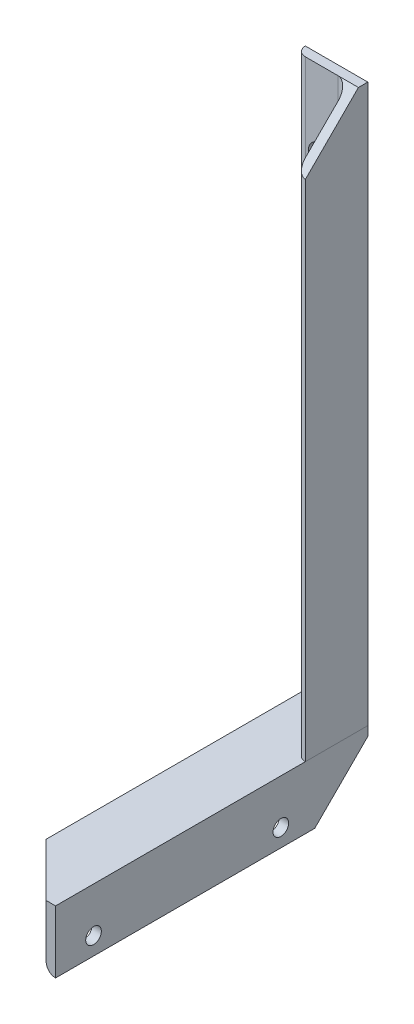
SolidWorks part; units mm, degrees
ref_plane "Plano frontal" through (0, 0, 0) normal (0, 0, 1) x (1, 0, 0)
ref_plane "Plano superior" through (0, 0, 0) normal (0, 1, 0) x (1, 0, 0)
ref_plane "Plano direito" through (0, 0, 0) normal (1, 0, 0) x (0, 0, -1)
sketch3d "3DSketch3"
  line L0 (-88.2895, 161.7817, 0) -> (-88.2895, -16.7183, 0)
  line L1 (-88.2895, -16.7183, 0) -> (-88.2895, -16.7183, 100)
  point P3 (-88.2895, 161.7817, 0)
  point P4 (0, 0, 0)
  dimension "D1" = 178.5
other "L angle (equal) 20X20X3(3)"
ref_plane "Plano1" through (-88.2895, 161.7817, 0) normal (0, 1, 0) x (-1, 0, 0)
sketch "Sketch1" plane through (-88.2895, 161.7817, 0) normal (0, 1, 0) x (-1, 0, 0)
  line L0 (0, 20) -> (0, 0)
  line L2 (3, 17) -> (3, 6.5)
  line L3 (6.5, 3) -> (17, 3)
  line L5 (20, 0) -> (0, 0)
  arc A0 (3, 17) -> (0, 20) centre (0, 17) ccw
  arc A1 (20, 0) -> (17, 3) centre (17, 0) ccw
  arc A2 (6.5, 3) -> (3, 6.5) centre (6.5, 6.5) cw
  point P8 (0, 10)
  point P9 (10, 0)
  point P10 (0, 0)
  dimension "Radius_2" = 3
  dimension "Radius_1" = 3.5
  dimension "V_leg" = 20
  dimension "H_leg" = 20
  dimension "thickness" = 3
sketch "Esboço3" plane through (0, 0, 3) normal (0, 0, 1) x (1, 0, 0)
  circle A0 centre (-100.6368, 76.4548) radius 3.5
  circle A1 centre (-100.6368, 136.4548) radius 3.6727
extrude "Corte-extrusão1" cut sketch "Esboço3" against normal blind 200
sketch "Esboço4" plane through (-88.2895, -131.681, 0) normal (1, 0, 0) x (0, 0, -1)
  circle A0 centre (-87.8431, 100.6358) radius 2.5
  circle A1 centre (-27.8431, 100.6358) radius 2.5
  point P6 (-87.8431, 100.6358)
  point P7 (-27.8431, 100.6358)
extrude "Corte-extrusão2" cut sketch "Esboço4" against normal blind 10
sketch "Esboço5" plane through (-88.2895, 0, 0) normal (1, 0, 0) x (0, 0, -1)
  line L0 (-3, 161.7817) -> (-20, 161.7817)
  line L1 (-20, 161.7817) -> (-20, 144.7817)
  line L2 (-20, -36.7183) -> (-20, 161.7817) construction
  line L3 (-20, 144.7817) -> (-3, 161.7817)
  point P4 (-6.5, 161.7817)
  point P8 (-3, 161.7817)
extrude "Corte-extrusão3" cut sketch "Esboço5" against normal blind 10
other "Aparar/Estender1"
sketch "Esboço8" plane through (0, -16.7183, 0) normal (0, 1, 0) x (1, 0, 0)
  line L0 (-91.2895, -100) -> (-108.2895, -83)
  line L1 (-108.2895, -100) -> (-108.2895, 0) construction
  line L2 (-108.2895, -83) -> (-108.2895, -100)
  line L3 (-108.2895, -100) -> (-91.2895, -100)
extrude "Corte-extrusão5" cut sketch "Esboço8" against normal blind 10
sketch "Esboço9" plane through (-88.2895, 0, 0) normal (1, 0, 0) x (0, 0, -1)
  line L0 (0, -19.7183) -> (-17, -36.7183)
  line L1 (-100, -36.7183) -> (0, -36.7183) construction
  line L2 (-17, -36.7183) -> (0, -36.7183)
  line L3 (0, -36.7183) -> (0, -19.7183)
extrude "Corte-extrusão6" cut sketch "Esboço9" against normal blind 10
